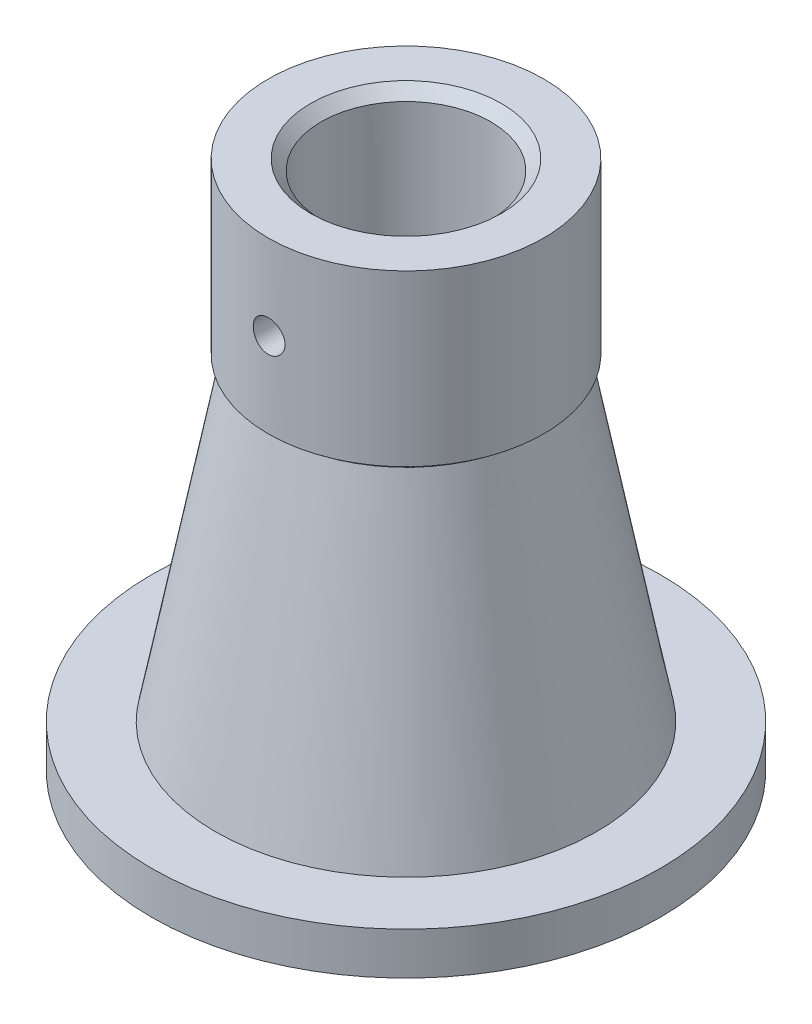
SolidWorks part; units mm, degrees
ref_plane "Front Plane" through (0, 0, 0) normal (0, 0, 1) x (1, 0, 0)
ref_plane "Top Plane" through (0, 0, 0) normal (0, 1, 0) x (1, 0, 0)
ref_plane "Right Plane" through (0, 0, 0) normal (1, 0, 0) x (0, 0, -1)
sketch "Sketch1" plane through (0, 0, 0) normal (0, 0, 1) x (1, 0, 0)
  line L0 (0, 126.4348) -> (0, -95.1304) construction
  line L1 (-190.6087, 0) -> (60.8696, 0) construction
  line L2 (80, 0) -> (120, 0)
  line L3 (120, 0) -> (120, 20)
  line L4 (120, 20) -> (90, 20)
  line L5 (90, 20) -> (61.86, 167.5415)
  line L6 (63.8661, 170) -> (65, 170)
  line L7 (65, 170) -> (65, 250)
  line L8 (65, 250) -> (40, 250)
  line L9 (40, 250) -> (40, 170)
  line L10 (40, 170) -> (45, 170)
  line L12 (48.1268, 167.1155) -> (80, 0)
  line L13 (80, 0) -> (209.0435, 0) construction
  arc A0 (63.8661, 170) -> (61.86, 167.5415) centre (66.5368, 165.773) ccw
  arc A1 (45, 170) -> (48.1268, 167.1155) centre (43.4951, 165.2318) cw
  dimension "D7" = 150
  dimension "D8" = 5
  dimension "D11" = 5
  dimension "D1" = 20
  dimension "D2" = 10
  dimension "D3" = 80
  dimension "D4" = 40
  dimension "D5" = 65
  dimension "D6" = 45
  dimension "D9" = 80
  dimension "D10" = 120
revolve "Revolve1" add sketch "Sketch1" angle 360 about L0
chamfer "Chamfer1" distance 5 angle 45 1 edges at (0, 250, 40)
sketch "Sketch2" plane through (0, 0, 0) normal (0, 0, 1) x (1, 0, 0)
  line L0 (0, 258.5405) -> (0, -15.433) construction
  line L1 (-65, 210) -> (80.9859, 210) construction
  line L2 (-65, 250) -> (-65, 170) construction
  circle A0 centre (0, 210) radius 7.5
  dimension "D1" = 15
extrude "Cut-Extrude1" cut sketch "Sketch2" along normal up to next
cosmetic thread "Cosmetic Thread1" parameters "D2"=18
